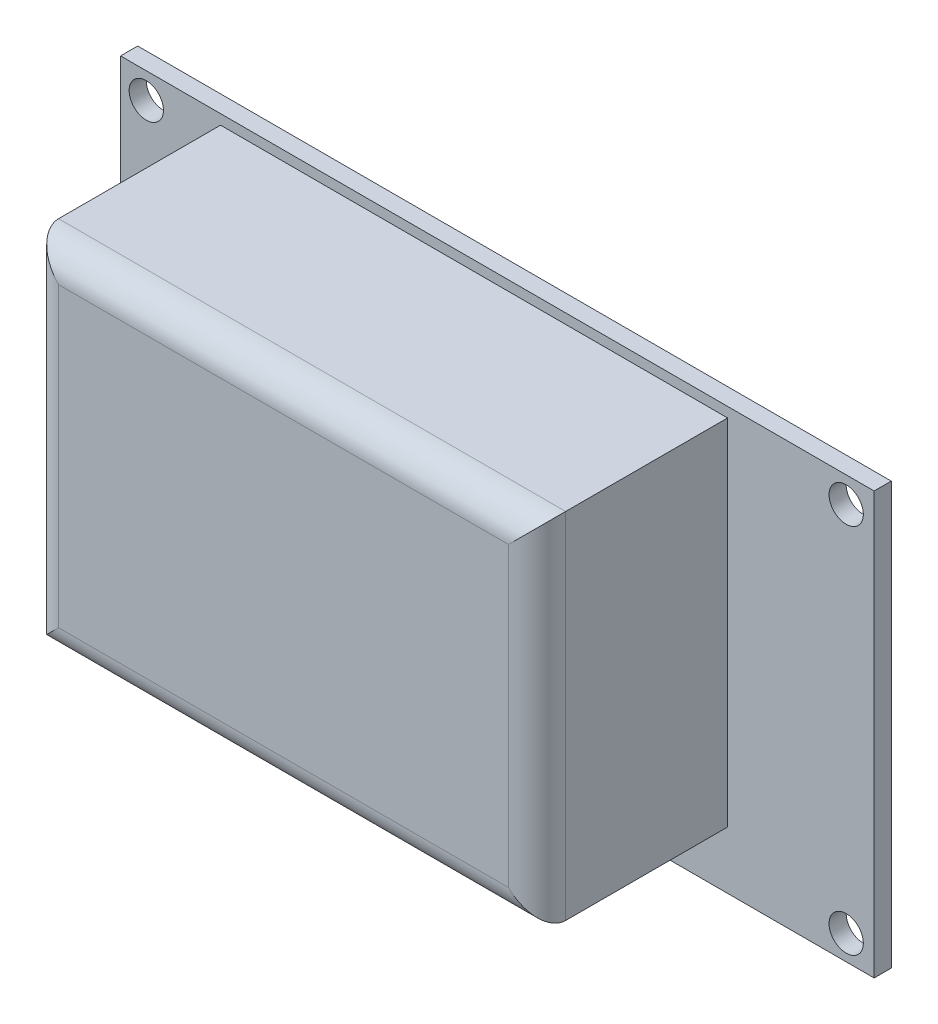
SolidWorks part; units mm, degrees
ref_plane "Front Plane" through (0, 0, 0) normal (0, 0, 1) x (1, 0, 0)
ref_plane "Top Plane" through (0, 0, 0) normal (0, 1, 0) x (1, 0, 0)
ref_plane "Right Plane" through (0, 0, 0) normal (1, 0, 0) x (0, 0, -1)
sketch "Sketch1" plane through (0, 0, 0) normal (0, 0, 1) x (1, 0, 0)
  line L1 (-33.5, 18.75) -> (33.5, 18.75)
  line L2 (-33.5, 18.75) -> (-33.5, -18.75)
  line L3 (-33.5, -18.75) -> (33.5, -18.75)
  line L4 (33.5, 18.75) -> (33.5, -18.75)
  line L6 (0, -55) -> (0, 55) construction
  line L7 (55, 0) -> (-55, 0) construction
  point P4 (0, 18.75)
  point P7 (-33.5, 0)
  dimension "D1" = 67
  dimension "D2" = 37.5
  dimension "D4" = 2
extrude "Boss-Extrude1" add sketch "Sketch1" along normal blind 1.524
sketch "Sketch2" plane through (0, 0, 1.524) normal (0, 0, 1) x (1, 0, 0)
  line L1 (33.5, 18.75) -> (-33.5, 18.75) construction
  line L2 (-33.5, 18.75) -> (-33.5, -18.75) construction
  circle A0 centre (-31.214, 16.464) radius 1.524
  circle A1 centre (31.016, 16.464) radius 1.524
  circle A2 centre (-31.214, -16.556) radius 1.524
  circle A3 centre (31.016, -16.556) radius 1.524
  dimension "D1" = 2
  dimension "D3" = 2.286
  dimension "D4" = 2.286
  dimension "D2" = 2
extrude "Cut-Extrude1" cut sketch "Sketch2" against normal blind 1.524
sketch "Sketch3" plane through (0, 0, 1.524) normal (0, 0, 1) x (1, 0, 0)
  line L0 (33.5, 18.75) -> (-33.5, 18.75) construction
  line L1 (-24.61, 17.861) -> (20.475, 17.861)
  line L2 (-24.61, 17.861) -> (-24.61, -13.635)
  line L3 (-24.61, -13.635) -> (20.475, -13.635)
  line L4 (20.475, 17.861) -> (20.475, -13.635)
  line L5 (-33.5, 18.75) -> (-33.5, -18.75) construction
  dimension "D1" = 45.085
  dimension "D2" = 31.496
  dimension "D3" = 0.889
  dimension "D4" = 8.89
extrude "Boss-Extrude2" add sketch "Sketch3" along normal blind 16.9418
fillet "Fillet1" radius 2.54 4 edges at (-24.61, 2.113, 18.4658) (-2.0675, -13.635, 18.4658) (20.475, 2.113, 18.4658) (-2.0675, 17.861, 18.4658)
